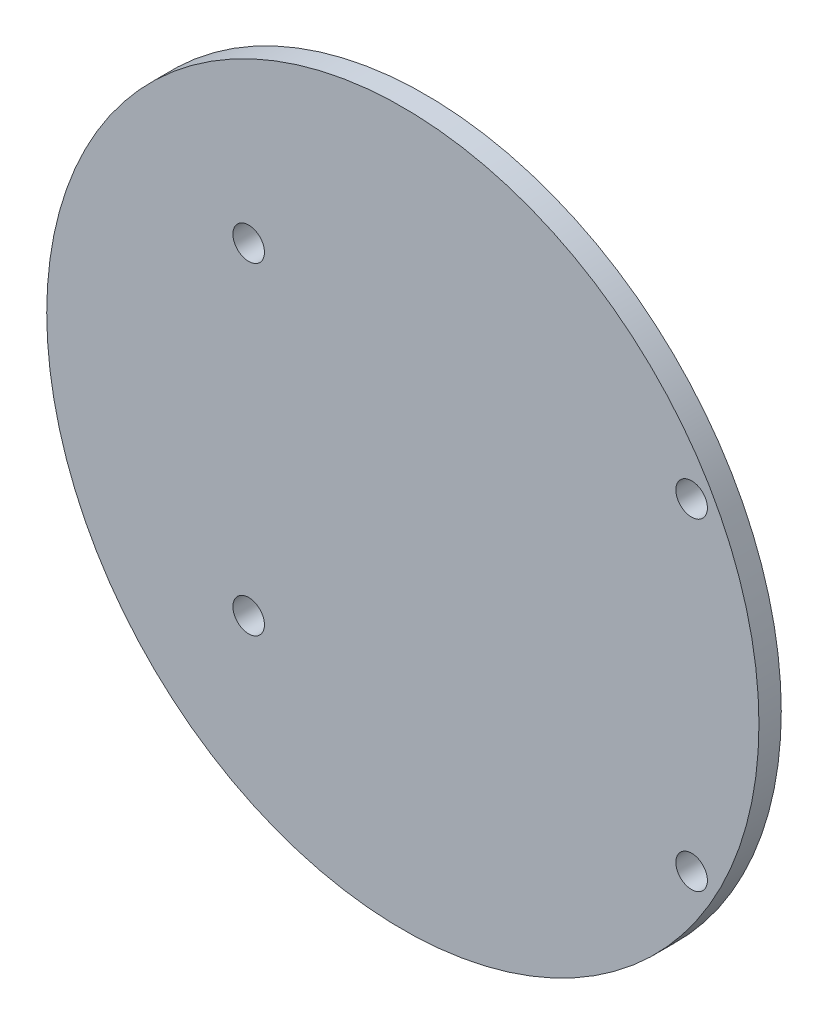
SolidWorks part; units mm, degrees
ref_plane "Front Plane" through (0, 0, 0) normal (0, 0, 1) x (1, 0, 0)
ref_plane "Top Plane" through (0, 0, 0) normal (0, 1, 0) x (1, 0, 0)
ref_plane "Right Plane" through (0, 0, 0) normal (1, 0, 0) x (0, 0, -1)
sketch "Sketch1" plane through (0, 0, 0) normal (0, 0, 1) x (1, 0, 0)
  circle A0 centre (27.94, 27.94) radius 25.527
  dimension "D1" = 51.054
extrude "BOARD" add sketch "Sketch1" along normal blind 1.6 separate body
sketch "Sketch2" plane through (0, 0, 0) normal (0, 0, 1) x (1, 0, 0)
  circle A0 centre (48.64, 39.5) radius 1.13
  circle A1 centre (48.64, 16.38) radius 1.13
  circle A2 centre (16.89, 39.5) radius 1.13
  circle A3 centre (16.89, 16.38) radius 1.13
extrude "NON-PLATED HOLES" cut sketch "Sketch2" along normal through all
ref_plane "Plane1" through (0, 0, 2.4) normal (0, 0, 1) x (1, 0, 0)
